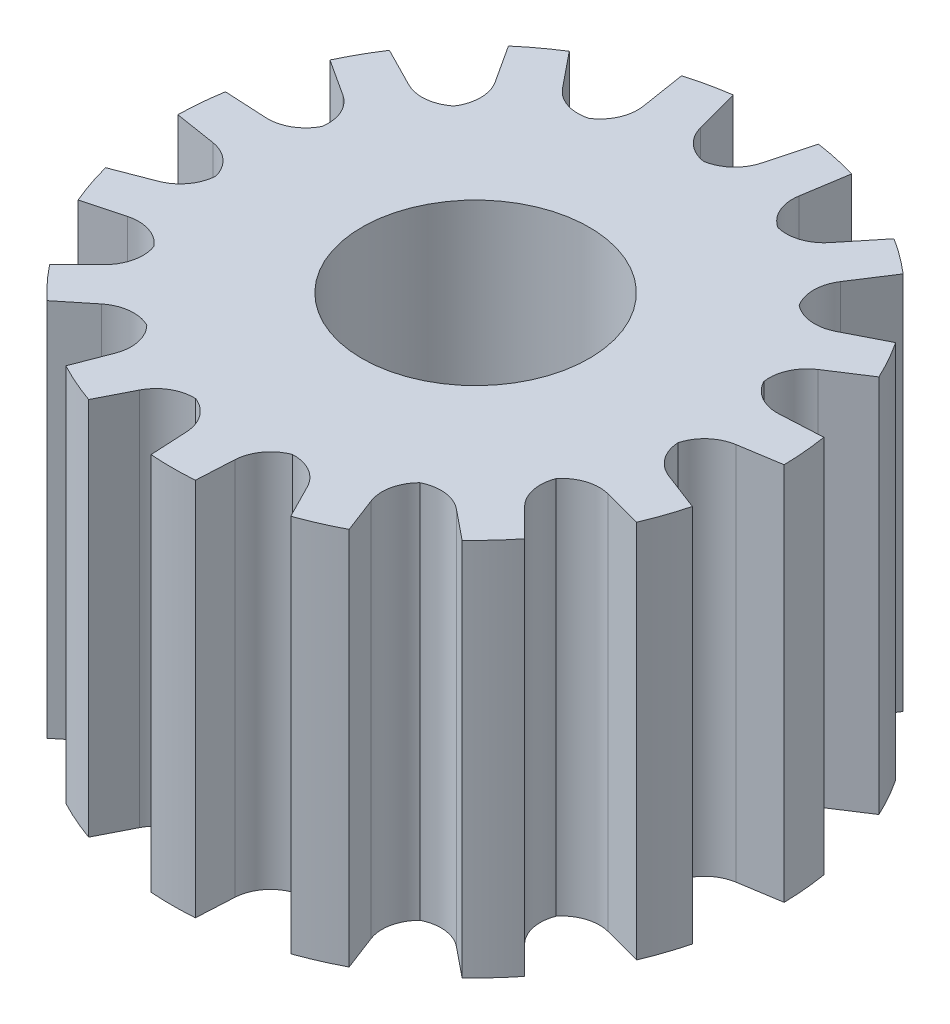
SolidWorks part; units mm, degrees
ref_plane "Plan de face" through (0, 0, 0) normal (0, 0, 1) x (1, 0, 0)
ref_plane "Plan de dessus" through (0, 0, 0) normal (0, 1, 0) x (1, 0, 0)
ref_plane "Plan de droite" through (0, 0, 0) normal (1, 0, 0) x (0, 0, -1)
sketch "Esquisse1" plane through (0, 0, 0) normal (0, 1, 0) x (1, 0, 0)
  circle A0 centre (0, 0) radius 20
  dimension "D1" = 40
extrude "Boss.-Extru.1" add sketch "Esquisse1" along normal blind 25
sketch "Esquisse3" plane through (0, 25, 0) normal (0, 1, 0) x (1, 0, 0)
  line L0 (0, 57.1636) -> (0, -16.0557) construction
  line L1 (-2.8069, 19.8021) -> (-2.0154, 16.8484)
  line L2 (2.8069, 19.8021) -> (1.5, 14.9248)
  arc A0 (1.5, 14.9248) -> (0.3423, 14.9961) centre (0, 0) ccw
  circle A1 centre (0, 0) radius 20 construction
  arc A2 (-2.0154, 16.8484) -> (0.3423, 14.9961) centre (0.3994, 17.4954) ccw
  circle A3 centre (0, 0) radius 20
  circle A4 centre (0, 0) radius 20
  arc A5 (2.0154, 16.8484) -> (-0.3423, 14.9961) centre (-0.3994, 17.4954) cw
  point P12 (-1.5, 14.9248)
  point P19 (7.8571, 40.0353)
  circle M1 centre (0, 0) radius 20
  dimension "D5" = 2.5
  dimension "D6" = 15
  dimension "D2" = 1.5
  dimension "D3" = 15
  dimension "D4" = 0
extrude "Enlèv. mat.-Extru.1" cut sketch "Esquisse3" against normal up to next contours L0 A4 L1 A2 A0 | L0 A0 A5 L2 M1
pattern_circular "Répétition circulaire1" count 16 every 24 about axis through (0, 0, 0.291) along (0, 1, 0) of "Enlèv. mat.-Extru.1"
sketch "Esquisse5" plane through (0, 25, 0) normal (0, 1, 0) x (1, 0, 0)
  circle A0 centre (0, 0) radius 7.5
  dimension "D1" = 15
extrude "Enlèv. mat.-Extru.2" cut sketch "Esquisse5" against normal up to next
